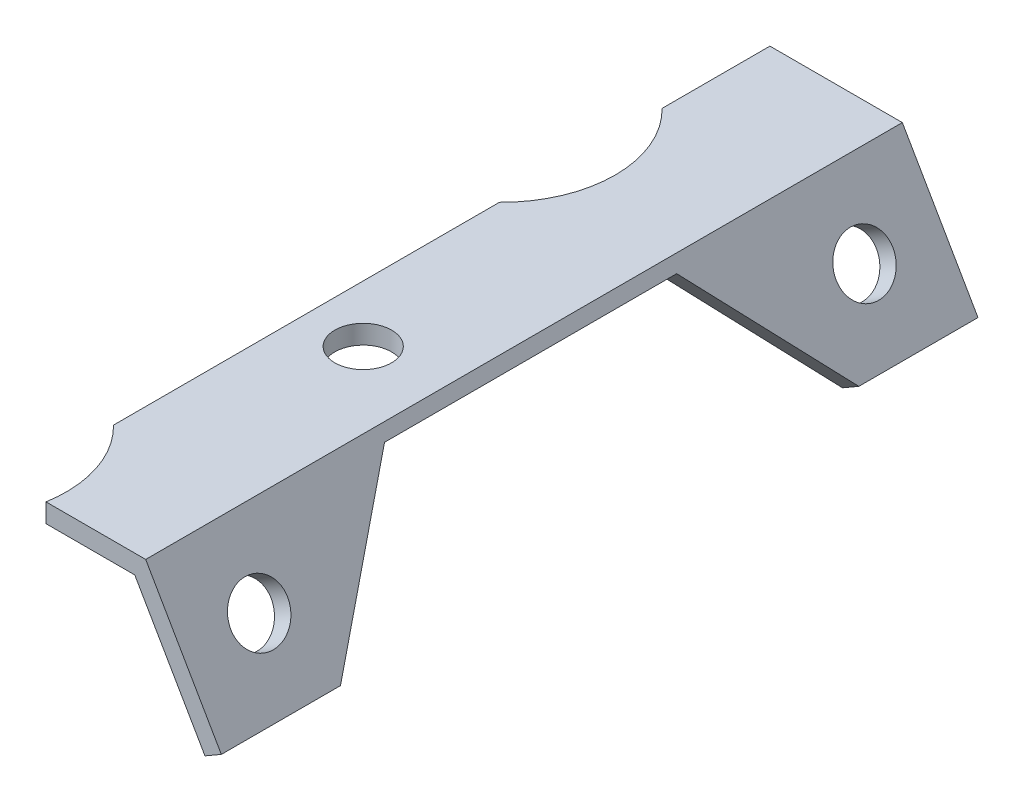
SolidWorks part; units mm, degrees
ref_plane "Front Plane" through (0, 0, 0) normal (0, 0, 1) x (1, 0, 0)
ref_plane "Top Plane" through (0, 0, 0) normal (0, 1, 0) x (1, 0, 0)
ref_plane "Right Plane" through (0, 0, 0) normal (1, 0, 0) x (0, 0, -1)
sketch "Sketch1" plane through (0, 0, 0) normal (0, 0, 1) x (1, 0, 0)
  line L0 (0, 13) -> (0, 14)
  line L1 (0, 14) -> (7, 14)
  line L2 (7, 14) -> (11, 7.0718)
  line L4 (1, 13) -> (6.4226, 13)
  line L5 (6.4226, 13) -> (10.134, 6.5718)
  line L7 (10.134, 6.5718) -> (11, 7.0718)
  line L8 (1, 13) -> (0, 13)
  line L9 (0, 4) -> (0, 14) construction
  line L10 (1, 4) -> (1, 13) construction
  dimension "D1" = 1
extrude "Boss-Extrude1" add sketch "Sketch1" along normal blind 40
sketch "Sketch3" plane through (11.3122, 6.5311, 0) normal (0.866, 0.5, 0) x (0, 0, -1)
  line L0 (-40, 0.6244) -> (-40, 8.6244) construction
  line L1 (-40, 8.6244) -> (0, 8.6244) construction
  line L2 (0, 0.6244) -> (0, 8.6244) construction
  line L3 (-33.7015, 0.6244) -> (-27.7217, 7.9274)
  line L4 (-40, 0.6244) -> (0, 0.6244) construction
  line L5 (-20, 12.1244) -> (-20, -2.4377) construction
  line L6 (-40, 12.1244) -> (0, 12.1244) construction
  line L7 (-27.7217, 7.9274) -> (-12.2783, 7.9274)
  line L8 (-33.7015, 0.6244) -> (-6.2985, 0.6244)
  line L9 (-6.2985, 0.6244) -> (-12.2783, 7.9274)
  circle A0 centre (-36, 4.6244) radius 1.5
  circle A1 centre (-4, 4.6244) radius 1.5
  point P21 (-20, 0.6244)
  point P22 (-20, 7.9274)
  dimension "D1" = 4
  dimension "D3" = 4
  dimension "D2" = 4
extrude "Cut-Extrude2" cut sketch "Sketch3" against normal blind 1
sketch "Sketch4" plane through (0, 14, 0) normal (0, 1, 0) x (-1, 0, 0)
  line L0 (-7, 0) -> (0, 0) construction
  line L1 (0, 40) -> (0, 0) construction
  circle A0 centre (-3, 24.5) radius 1.5
  circle A1 centre (4.1857, 10) radius 6
  circle A2 centre (4.1857, 39) radius 6
  dimension "D1" = 24.5
  dimension "D3" = 10
  dimension "D4" = 29
  dimension "D2" = 3
extrude "Cut-Extrude3" cut sketch "Sketch4" against normal blind 10
